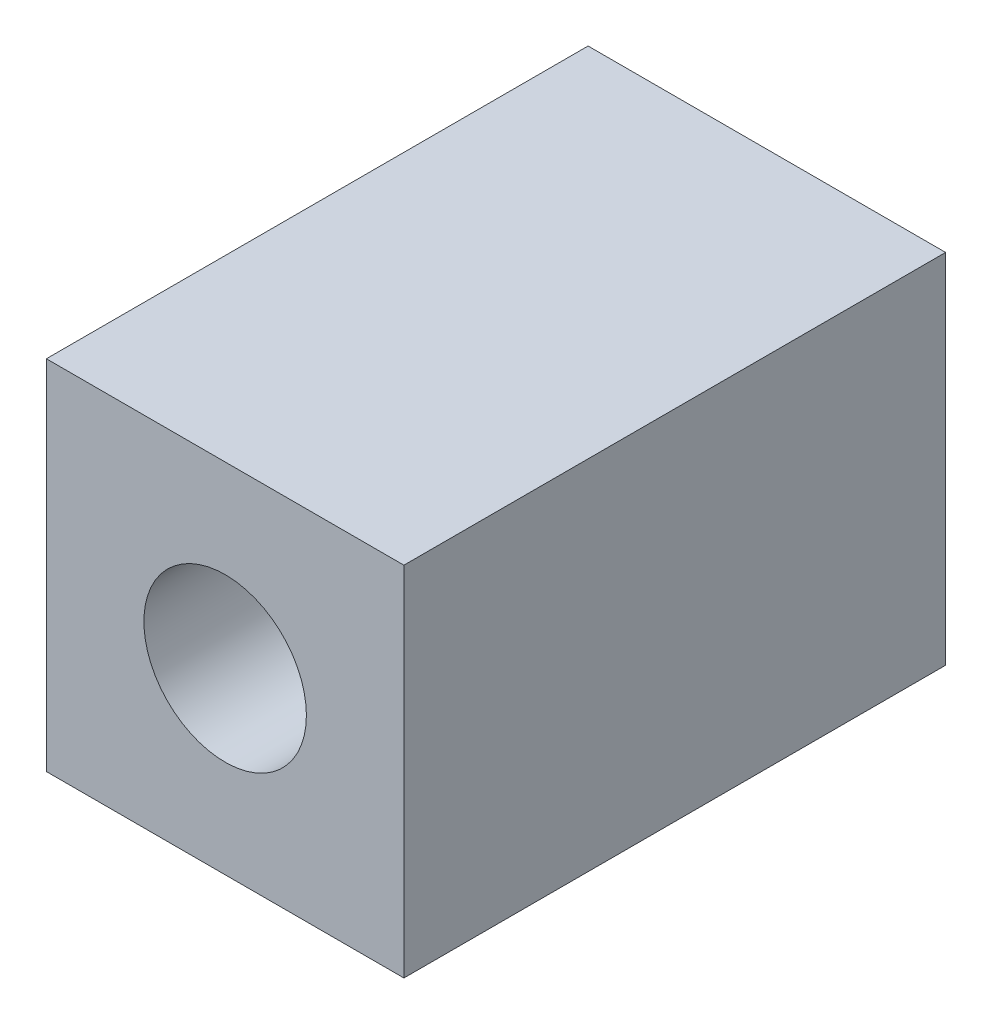
SolidWorks part; units mm, degrees
ref_plane "Alzado" through (0, 0, 0) normal (0, 0, 1) x (1, 0, 0)
ref_plane "Planta" through (0, 0, 0) normal (0, 1, 0) x (1, 0, 0)
ref_plane "Vista lateral" through (0, 0, 0) normal (1, 0, 0) x (0, 0, -1)
sketch "Croquis1" plane through (0, 0, 0) normal (0, 0, 1) x (1, 0, 0)
  line L1 (-20.8921, 4.3805) -> (-14.2921, 4.3805)
  line L2 (-20.8921, 4.3805) -> (-20.8921, -2.2195)
  line L3 (-20.8921, -2.2195) -> (-14.2921, -2.2195)
  line L4 (-14.2921, 4.3805) -> (-14.2921, -2.2195)
  dimension "D1" = 6.6
  dimension "D2" = 6.6
extrude "Saliente-Extruir1" add sketch "Croquis1" along normal blind 10
sketch "Croquis2" plane through (0, 0, 10) normal (0, 0, 1) x (1, 0, 0)
  line L0 (-20.8921, -2.2195) -> (-14.2921, 4.3805) construction
  circle A0 centre (-17.5921, 1.0805) radius 1.5
  dimension "D1" = 3
extrude "Cortar-Extruir1" cut sketch "Croquis2" against normal blind 4
sketch "Croquis3" plane through (0, 0, 0) normal (0, 0, -1) x (-1, 0, 0)
  line L0 (20.8921, 4.3805) -> (14.2921, -2.2195) construction
  line L2 (15.9921, 2.6805) -> (19.1921, 2.6805)
  line L3 (15.9921, 2.6805) -> (15.9921, -0.5195)
  line L4 (15.9921, -0.5195) -> (19.1921, -0.5195)
  line L5 (19.1921, 2.6805) -> (19.1921, -0.5195)
  line L6 (15.9921, 2.6805) -> (19.1921, -0.5195) construction
  line L7 (15.9921, -0.5195) -> (19.1921, 2.6805) construction
  point P4 (17.5921, 1.0805)
  dimension "D1" = 3.2
  dimension "D2" = 3.2
extrude "Cortar-Extruir2" cut sketch "Croquis3" against normal blind 4
